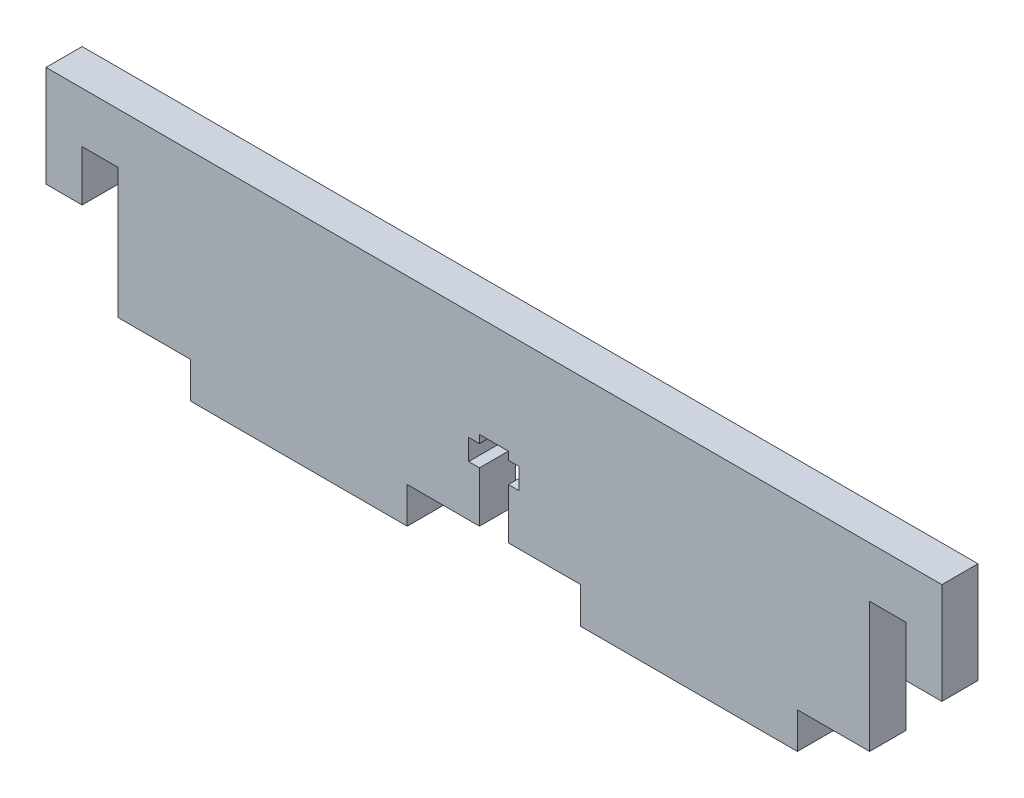
SolidWorks part; units mm, degrees
ref_plane "前视基准面" through (0, 0, 0) normal (0, 0, 1) x (1, 0, 0)
ref_plane "上视基准面" through (0, 0, 0) normal (0, 1, 0) x (1, 0, 0)
ref_plane "右视基准面" through (0, 0, 0) normal (1, 0, 0) x (0, 0, -1)
sketch "草图1" plane through (0, 0, 0) normal (0, 0, 1) x (1, 0, 0)
  line L0 (-54, 0) -> (-50, 0)
  line L1 (0, 0) -> (-104, 0)
  line L2 (0, 0) -> (0, 25)
  line L3 (0, 25) -> (-104, 25)
  line L4 (-104, 0) -> (-104, 25)
  line L5 (-94, 0) -> (-64, 0)
  line L6 (-94, 0) -> (-94, -5)
  line L7 (-94, -5) -> (-64, -5)
  line L8 (-64, 0) -> (-64, -5)
  line L9 (-40, 0) -> (-10, 0)
  line L10 (-40, 0) -> (-40, -5)
  line L11 (-40, -5) -> (-10, -5)
  line L12 (-10, 0) -> (-10, -5)
  line L13 (-54, 0) -> (-54, 11)
  line L14 (-54, 11) -> (-50, 11)
  line L15 (-50, 0) -> (-50, 11)
  line L16 (-55.5, 9.9) -> (-48.5, 9.9)
  line L17 (-55.5, 9.9) -> (-55.5, 7)
  line L18 (-55.5, 7) -> (-48.5, 7)
  line L19 (-48.5, 9.9) -> (-48.5, 7)
  line L20 (-52, 25) -> (-52, -9.611) construction
  line L21 (-104, 25) -> (-109, 25)
  line L22 (-104, 25) -> (-104, 18)
  line L23 (-104, 18) -> (-109, 18)
  line L25 (-114, 25) -> (-109, 25)
  line L26 (-114, 25) -> (-114, 11)
  line L27 (-114, 11) -> (-109, 11)
  line L28 (-109, 25) -> (-109, 11)
  line L30 (10, 11) -> (5, 11)
  line L31 (10, 25) -> (10, 11)
  line L32 (10, 25) -> (5, 25)
  line L33 (5, 25) -> (5, 11)
  line L34 (0, 18) -> (5, 18)
  line L35 (0, 25) -> (5, 25)
  point P13 (-94, -2.5)
  point P22 (-55.5, 8.45)
  point P37 (0, 0)
  dimension "D1" = 5
  dimension "D2" = 5
  dimension "D3" = 10
  dimension "D4" = 104
  dimension "D5" = 25
  dimension "D6" = 10
  dimension "D7" = 30
  dimension "D8" = 30
  dimension "D9" = 4
  dimension "D10" = 7
  dimension "D11" = 2.9
  dimension "D12" = 1.5
  dimension "D13" = 0
  dimension "D14" = 11
  dimension "D15" = 7
  dimension "D16" = 10
  dimension "D17" = 5
  dimension "D18" = 5
  dimension "D19" = 14
  dimension "D20" = 7
extrude "凸台-拉伸2" add sketch "草图1" along normal blind 5 contours L21 L28 L23 L4 | L28 L25 L26 L27 | L20 L3 L4 L1 L13 L18 L17 L16 L14 | L3 L20 L14 L15 L16 L19 L18 L1 L2 | L32 L33 L30 L31 | L35 L2 L34 L33 | L12 L1 L10 L11 | L8 L1 L6 L7
